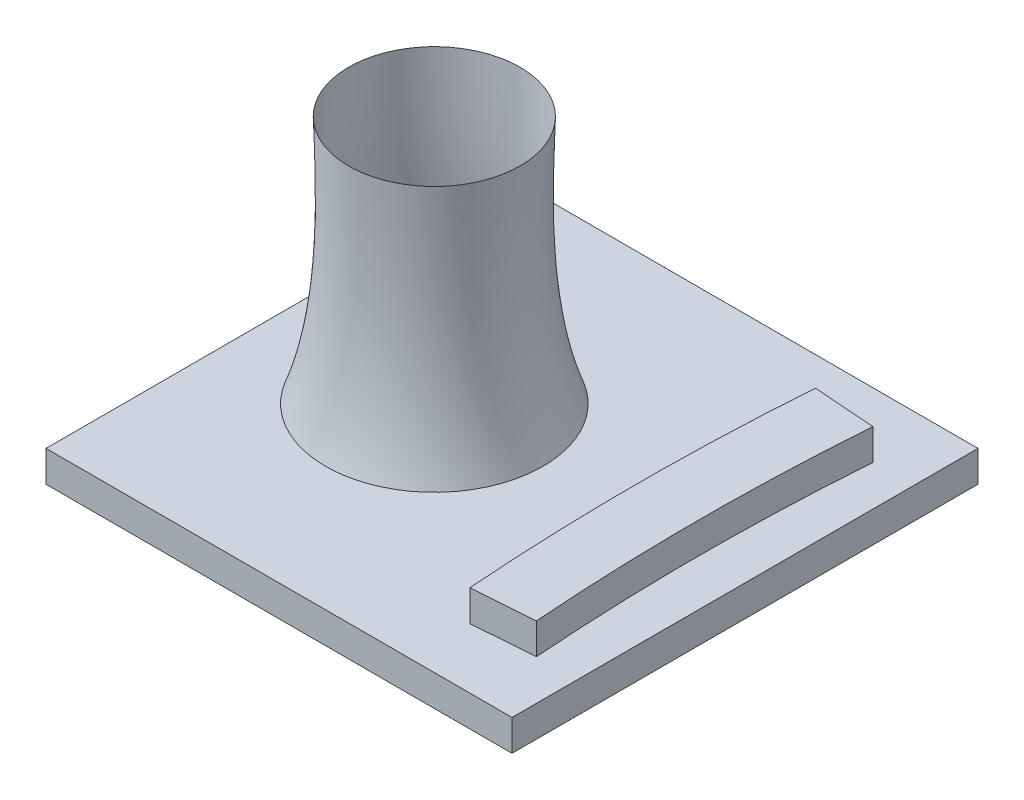
SolidWorks part; units mm, degrees
ref_plane "Front Plane" through (0, 0, 0) normal (0, 0, 1) x (1, 0, 0)
ref_plane "Top Plane" through (0, 0, 0) normal (0, 1, 0) x (1, 0, 0)
ref_plane "Right Plane" through (0, 0, 0) normal (1, 0, 0) x (0, 0, -1)
sketch "Sketch1" plane through (0, 0, 0) normal (0, 1, 0) x (1, 0, 0)
  line L1 (0, 0) -> (150, 0)
  line L2 (0, 0) -> (0, -150)
  line L3 (0, -150) -> (150, -150)
  line L4 (150, 0) -> (150, -150)
  circle A0 centre (50, -75) radius 35
  dimension "D3" = 70
  dimension "D1" = 150
  dimension "D2" = 150
  dimension "D4" = 50
  dimension "D5" = 75
extrude "Boss-Extrude1" add sketch "Sketch1" along normal blind 10
ref_plane "Plane1" through (0, -10, 0) normal (0, -1, 0) x (-1, 0, 0)
ref_plane "Plane2" through (0, 90, 0) normal (0, 1, 0) x (1, 0, 0)
sketch "Sketch3" plane through (0, -10, 0) normal (0, -1, 0) x (-1, 0, 0)
  circle A0 centre (-50, -75) radius 48.2166
sketch "Sketch4" plane through (0, 90, 0) normal (0, 1, 0) x (1, 0, 0)
  circle A0 centre (50, -75) radius 27.5696
sketch "Sketch5" plane through (0, 10, 0) normal (0, 1, 0) x (1, 0, 0)
  circle A0 centre (50, -75) radius 35
surface "Surface-Loft1"
sketch "Sketch7" plane through (0, 10, 0) normal (0, 1, 0) x (1, 0, 0)
  line L0 (150, 0) -> (0, -150) construction
  line L1 (0, -150) -> (150, -150) construction
  line L2 (150, -150) -> (0, 0) construction
  line L3 (115, -150) -> (115, 0) construction
  line L4 (150, 0) -> (0, 0) construction
  line L5 (150, -150) -> (150, 0) construction
  line L6 (117.0656, -19.3745) -> (137.0106, -20.8579)
  line L7 (75, -75) -> (182.4047, -75) construction
  line L8 (117.0656, -130.6255) -> (137.0106, -129.1421)
  arc A0 (117.0656, -19.3745) -> (117.0656, -130.6255) centre (865, -75) ccw
  arc A1 (137.0106, -20.8579) -> (137.0106, -129.1421) centre (865, -75) ccw
  circle A2 centre (865, -75) radius 750 construction
  circle A3 centre (865, -75) radius 730 construction
  arc A4 (137.0106, -20.8579) -> (135, -75) centre (865, -75) cw construction
  point P16 (115, -75)
  dimension "D2" = 1500
  dimension "D1" = 35
  dimension "D3" = 20
extrude "Boss-Extrude2" add sketch "Sketch7" along normal blind 10
